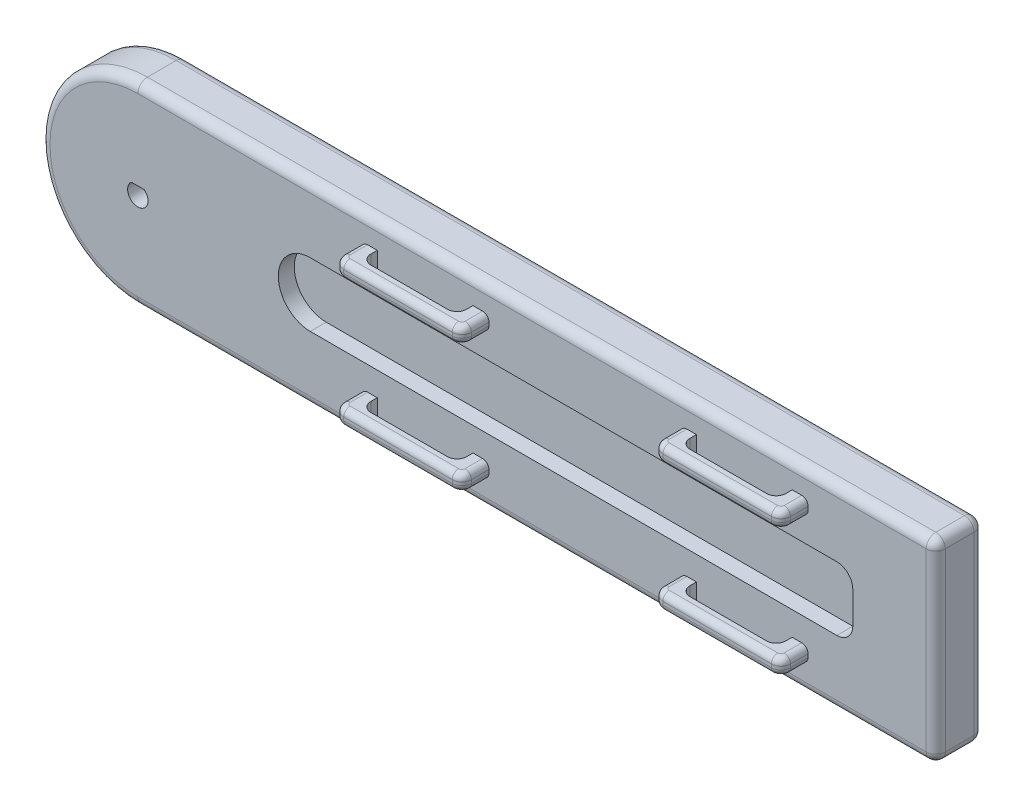
SolidWorks part; units mm, degrees
ref_plane "Front Plane" through (0, 0, 0) normal (0, 0, 1) x (1, 0, 0)
ref_plane "Top Plane" through (0, 0, 0) normal (0, 1, 0) x (1, 0, 0)
ref_plane "Right Plane" through (0, 0, 0) normal (1, 0, 0) x (0, 0, -1)
sketch "Sketch1" plane through (0, 0, 0) normal (0, 0, 1) x (1, 0, 0)
  line L0 (0, 30.56) -> (250, 30.56)
  line L1 (250, 30.56) -> (250, -30.56)
  line L2 (250, -30.56) -> (0, -30.56)
  arc A0 (0, 30.56) -> (0, -30.56) centre (0, 0) ccw
  dimension "D1" = 30.56
  dimension "D2" = 250
  dimension "D3" = 250
extrude "Boss-Extrude1" add sketch "Sketch1" along normal blind 15
sketch "Sketch3" plane through (0, 0, 15) normal (0, 0, 1) x (1, 0, 0)
  line L0 (0, 0) -> (0, 13.5) construction
  line L1 (0, 0) -> (-11.6913, -6.75) construction
  line L2 (0, 0) -> (11.6913, -6.75) construction
  dimension "D1" = 13.5
  dimension "D2" = 13.5
  dimension "D3" = 13.5
  dimension "D4" = 120
  dimension "D5" = 120
ref_plane "Plan3" through (0, 22.56, 0) normal (0, 1, 0) x (1, 0, 0)
fillet "Congé2" radius 3 10 edges at (125, -30.56, 0) (-30.56, 0, 0) (125, 30.56, 0) (250, 0, 0) (125, 30.56, 15) (250, 0, 15) (125, -30.56, 15) (-30.56, 0, 15) (250, -30.56, 7.5) (250, 30.56, 7.5)
sketch "Esquisse5" plane through (0, 0, 15) normal (0, 0, 1) x (1, 0, 0)
  line L1 (-2.0243, 2.5223) -> (1.9757, 2.5223)
  arc A3 (1.9757, 2.5223) -> (-2.0243, 2.5223) centre (-0.0243, 0.0243) cw
  dimension "D1" = 3.2
  dimension "D2" = 4
extrude "Enlèv. mat.-Extru.3" cut sketch "Esquisse5" against normal blind 10
sketch "Esquisse9" plane through (0, 22.56, 0) normal (0, 1, 0) x (1, 0, 0)
  line L0 (70, -15) -> (70, -23.5)
  line L1 (0, -15) -> (11.6913, -15) construction
  line L2 (0, -15) -> (247, -15) construction
  line L3 (70, -23.5) -> (110, -23.5)
  line L4 (110, -23.5) -> (110, -15)
  line L5 (247, -15) -> (0, -15) construction
  line L6 (110, -15) -> (105, -15)
  line L7 (105, -15) -> (105, -20)
  line L8 (105, -20) -> (75, -20)
  line L9 (75, -20) -> (75, -15)
  line L10 (75, -15) -> (70, -15)
  dimension "D1" = 30
  dimension "D2" = 8.5
  dimension "D3" = 5
  dimension "D4" = 70
  dimension "D5" = 5
  dimension "D6" = 5
extrude "Boss.-Extru.1" add sketch "Esquisse9" against normal blind 5
fillet "Congé3" radius 3 1 edges at (70, 20.06, 23.5)
fillet "Congé4" radius 3 3 edges at (75, 20.06, 20) (105, 20.06, 20) (110, 20.06, 23.5)
pattern_linear "Répétition linéaire1" count 2 spacing 100 along (1, 0, 0) of "Boss.-Extru.1"
pattern_linear "Répétition linéaire2" count 2 spacing 40 along (0, -1, 0) of "Répétition linéaire1", "Boss.-Extru.1"
fillet "Congé5" radius 3 4 edges at (105, -19.94, 20) (75, -19.94, 20) (70, -19.94, 23.5) (110, -19.94, 23.5)
fillet "Congé6" radius 3 4 edges at (175, -19.94, 20) (205, -19.94, 20) (210, -19.94, 23.5) (170, -19.94, 23.5)
fillet "Congé7" radius 3 4 edges at (175, 20.06, 20) (205, 20.06, 20) (170, 20.06, 23.5) (210, 20.06, 23.5)
fillet "Congé8" radius 2 40 edges at (170, -17.44, 17.75) (170.8787, -17.44, 22.6213) (210, -17.44, 17.75) (209.1213, -17.44, 22.6213) (170, -22.44, 17.75) (170.8787, -22.44, 22.6213) (210, -22.44, 17.75) (209.1213, -22.44, 22.6213) (170, 17.56, 17.75) (170.8787, 17.56, 22.6213) (210, 17.56, 17.75) (209.1213, 17.56, 22.6213) (170, 22.56, 17.75) (170.8787, 22.56, 22.6213) (210, 22.56, 17.75) (209.1213, 22.56, 22.6213) (70, 22.56, 17.75) (70.8787, 22.56, 22.6213) (110, 22.56, 17.75) (109.1213, 22.56, 22.6213) (70, 17.56, 17.75) (70.8787, 17.56, 22.6213) (110, 17.56, 17.75) (109.1213, 17.56, 22.6213) (70, -22.44, 17.75) (70.8787, -22.44, 22.6213) (110, -22.44, 17.75) (109.1213, -22.44, 22.6213) (70, -17.44, 17.75) (70.8787, -17.44, 22.6213) (110, -17.44, 17.75) (109.1213, -17.44, 22.6213) (190, -17.44, 23.5) (190, -22.44, 23.5) (190, 17.56, 23.5) (190, 22.56, 23.5) (90, 22.56, 23.5) (90, 17.56, 23.5) (90, -22.44, 23.5) (90, -17.44, 23.5)
sketch "Esquisse11" plane through (0, 0, 15) normal (0, 0, 1) x (1, 0, 0)
  line L0 (54, 10.06) -> (224, 10.06)
  line L1 (224, 10.06) -> (224, -9.94)
  line L2 (224, -9.94) -> (54, -9.94)
  line L3 (247, 27.56) -> (0, 27.56) construction
  arc A0 (54, -9.94) -> (54, 10.06) centre (54, 0.06) cw
  dimension "D1" = 10
  dimension "D2" = 54
  dimension "D3" = 27.5
  dimension "D4" = 170
extrude "Enlèv. mat.-Extru.5" cut sketch "Esquisse11" against normal blind 5
fillet "Congé10" radius 5 2 edges at (224, -9.94, 12.5) (224, 10.06, 12.5)
